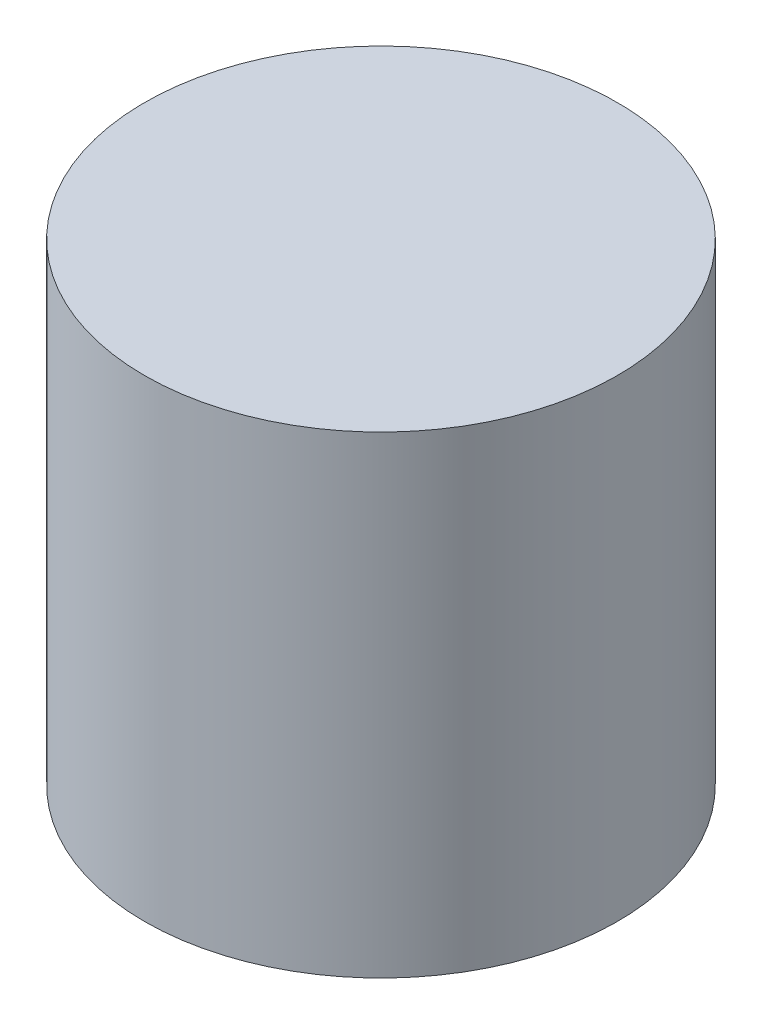
SolidWorks part; units mm, degrees
ref_plane "Front Plane" through (0, 0, 0) normal (0, 0, 1) x (1, 0, 0)
ref_plane "Top Plane" through (0, 0, 0) normal (0, 1, 0) x (1, 0, 0)
ref_plane "Right Plane" through (0, 0, 0) normal (1, 0, 0) x (0, 0, -1)
sketch "Sketch1" plane through (0, 0, 0) normal (0, 1, 0) x (1, 0, 0)
  circle A0 centre (0, 0) radius 4
  dimension "D1" = 8
extrude "Boss-Extrude1" add sketch "Sketch1" along normal blind 8
